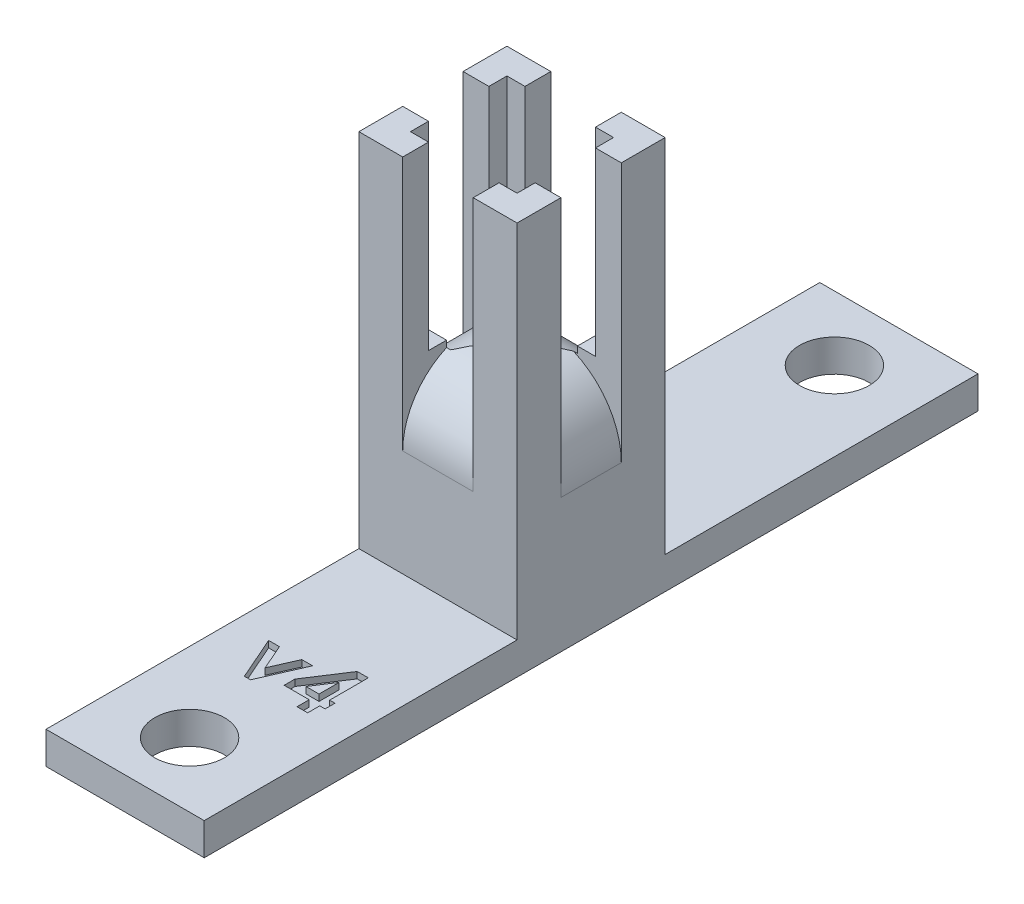
SolidWorks part; units mm, degrees
ref_plane "Front Plane" through (0, 0, 0) normal (0, 0, 1) x (1, 0, 0)
ref_plane "Top Plane" through (0, 0, 0) normal (0, 1, 0) x (1, 0, 0)
ref_plane "Right Plane" through (0, 0, 0) normal (1, 0, 0) x (0, 0, -1)
sketch "Sketch1" plane through (0, 0, 0) normal (0, 1, 0) x (1, 0, 0)
  line L0 (-5.25, 4.75) -> (-5.25, 2.972)
  line L1 (-5.25, -4.75) -> (5.25, -4.75) construction
  line L2 (-5.25, -4.75) -> (-5.25, 4.75) construction
  line L3 (-5.25, 4.75) -> (5.25, 4.75) construction
  line L4 (5.25, -4.75) -> (5.25, 4.75) construction
  line L5 (-5.25, -4.75) -> (5.25, 4.75) construction
  line L6 (-5.25, 4.75) -> (5.25, -4.75) construction
  line L7 (-5.25, 2.972) -> (-7.79, 2.972)
  line L8 (-7.79, 2.972) -> (-7.79, 7.29)
  line L9 (-7.79, 7.29) -> (-3.472, 7.29)
  line L10 (-3.472, 7.29) -> (-3.472, 4.75)
  line L11 (-3.472, 4.75) -> (-5.25, 4.75)
  line L12 (0, 4.75) -> (0, -4.75) construction
  line L13 (-5.25, 0) -> (5.25, 0) construction
  line L14 (7.79, 2.972) -> (7.79, 7.29)
  line L15 (5.25, 2.972) -> (7.79, 2.972)
  line L16 (5.25, 4.75) -> (5.25, 2.972)
  line L17 (3.472, 4.75) -> (5.25, 4.75)
  line L18 (3.472, 7.29) -> (3.472, 4.75)
  line L19 (7.79, 7.29) -> (3.472, 7.29)
  line L20 (5.25, -2.972) -> (7.79, -2.972)
  line L21 (5.25, -4.75) -> (5.25, -2.972)
  line L22 (3.472, -4.75) -> (5.25, -4.75)
  line L23 (3.472, -7.29) -> (3.472, -4.75)
  line L24 (7.79, -7.29) -> (3.472, -7.29)
  line L25 (7.79, -2.972) -> (7.79, -7.29)
  line L26 (-5.25, -2.972) -> (-7.79, -2.972)
  line L27 (-5.25, -4.75) -> (-5.25, -2.972)
  line L28 (-3.472, -4.75) -> (-5.25, -4.75)
  line L29 (-3.472, -7.29) -> (-3.472, -4.75)
  line L30 (-7.79, -7.29) -> (-3.472, -7.29)
  line L31 (-7.79, -2.972) -> (-7.79, -7.29)
  point P0 (0, 0)
  dimension "D1" = 10.5
  dimension "D2" = 9.5
  dimension "D3" = 2.54
  dimension "D4" = 1.778
extrude "Boss-Extrude1" add sketch "Sketch1" along normal blind 17.78
sketch "Sketch2" plane through (0, 0, 0) normal (0, -1, 0) x (-1, 0, 0)
  line L1 (7.79, -7.29) -> (-7.79, -7.29)
  line L2 (7.79, -7.29) -> (7.79, 7.29)
  line L3 (7.79, 7.29) -> (-7.79, 7.29)
  line L4 (-7.79, -7.29) -> (-7.79, 7.29)
extrude "Boss-Extrude2" add sketch "Sketch2" along normal blind 17.78
sketch "Sketch3" plane through (0, -17.78, 0) normal (0, -1, 0) x (-1, 0, 0)
  line L0 (0, 0) -> (7.79, 0) construction
  line L1 (-7.79, -38.1) -> (7.79, -38.1)
  line L2 (-7.79, -38.1) -> (-7.79, 38.1)
  line L3 (-7.79, 38.1) -> (7.79, 38.1)
  line L4 (7.79, -38.1) -> (7.79, 38.1)
  line L5 (-7.79, -38.1) -> (7.79, 38.1) construction
  line L6 (-7.79, 38.1) -> (7.79, -38.1) construction
  line L7 (7.79, -7.29) -> (7.79, 7.29) construction
  circle A0 centre (0, 31.75) radius 3.429
  circle A1 centre (0, -31.75) radius 3.429
  point P0 (0, 0)
  dimension "D2" = 6.858
  dimension "D3" = 31.75
  dimension "D4" = 76.2
extrude "Boss-Extrude3" add sketch "Sketch3" along normal blind 3.175
sketch "Sketch5" plane through (0, -17.78, 0) normal (0, 1, 0) x (1, 0, 0)
  line L0 (-7.79, -23.8163) -> (7.79, -23.8163) construction
  line L1 (-7.79, -38.1) -> (-7.79, -7.29) construction
  line L2 (7.79, -7.29) -> (7.79, -38.1) construction
  text T0 "<b>v4</b>" font "Century Gothic" height in points 22
extrude "Cut-Extrude3" cut sketch "Sketch5" against normal blind 0.635
sketch "Sketch6" plane through (0, 0, 0) normal (1, 0, 0) x (0, 0, -1)
  line L0 (7.29, 17.78) -> (7.29, -17.78) construction
  line L1 (-7.29, -7.29) -> (-7.29, 2.54)
  line L2 (-7.29, 2.54) -> (7.29, 2.54)
  line L3 (7.29, 2.54) -> (7.29, -7.29)
  line L4 (-7.29, -17.78) -> (-7.29, 17.78) construction
  arc A0 (7.29, -7.29) -> (-7.29, -7.29) centre (0, -7.29) ccw
  point P5 (-7.29, 2.9312)
  dimension "D1" = 2.54
extrude "Cut-Extrude4" cut sketch "Sketch6" against normal up to surface and the other way up to surface up to face at (-3.472, 8.89, 6.02) other way up to face at (3.472, 8.89, 6.02)
sketch "Sketch7" plane through (0, 0, 0) normal (0, 0, 1) x (1, 0, 0)
  line L0 (-7.79, -17.78) -> (-7.79, 17.78) construction
  line L1 (-7.79, -7.79) -> (-7.79, 4.5387)
  line L2 (-7.79, 4.5387) -> (7.79, 4.5387)
  line L3 (7.79, -17.78) -> (7.79, 17.78) construction
  line L4 (7.79, 4.5387) -> (7.79, -7.79)
  arc A0 (7.79, -7.79) -> (-7.79, -7.79) centre (0, -7.79) ccw
extrude "Cut-Extrude5" cut sketch "Sketch7" against normal up to surface and the other way up to surface up to face at (-6.52, 8.89, -2.972) other way up to face at (-6.52, 8.89, 2.972)
